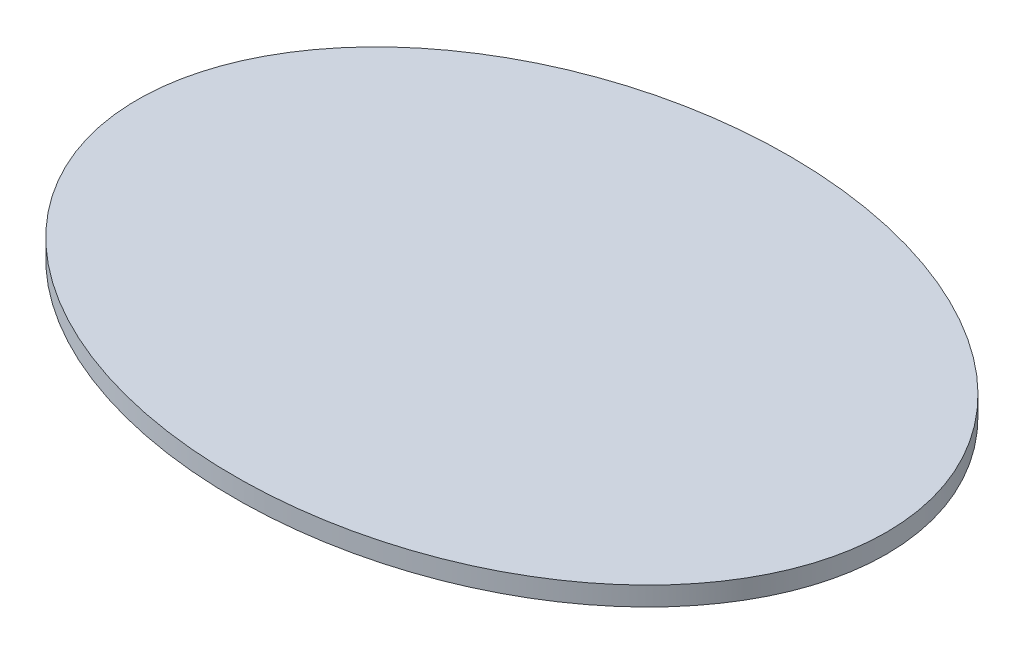
SolidWorks part; units mm, degrees
material "Acrylic (Medium-high impact)"
ref_plane "Front Plane" through (0, 0, 0) normal (0, 0, 1) x (1, 0, 0)
ref_plane "Top Plane" through (0, 0, 0) normal (0, 1, 0) x (1, 0, 0)
ref_plane "Right Plane" through (0, 0, 0) normal (1, 0, 0) x (0, 0, -1)
sketch "Sketch1" plane through (0, 0, 0) normal (0, 1, 0) x (1, 0, 0)
  ellipse E0 centre (0, 0) end of major axis (1000.633, 0) minor radius 740.9434
  dimension "D1" = 2001.266
  dimension "D2" = 1481.8868
extrude "Boss-Extrude1" add sketch "Sketch1" along normal blind 50.8
